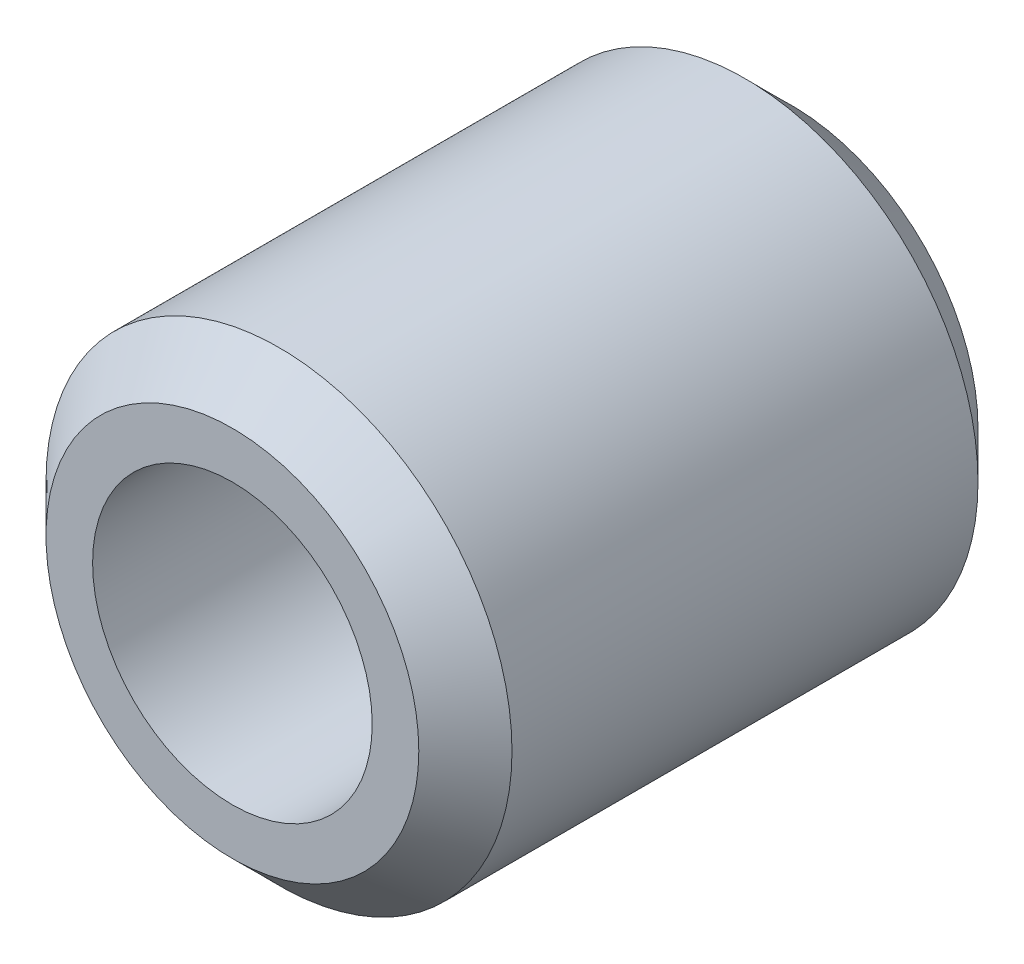
SolidWorks part; units mm, degrees
material "Alloy Steel"
ref_plane "Front Plane" through (0, 0, 0) normal (0, 0, 1) x (1, 0, 0)
ref_plane "Top Plane" through (0, 0, 0) normal (0, 1, 0) x (1, 0, 0)
ref_plane "Right Plane" through (0, 0, 0) normal (1, 0, 0) x (0, 0, -1)
sketch "Sketch1" plane through (0, 0, 0) normal (0, 0, 1) x (1, 0, 0)
  circle A0 centre (0, 0) radius 4.7625
  dimension "D1" = 9.525
extrude "Boss-Extrude1" add sketch "Sketch1" against normal blind 19.05
sketch "Sketch2" plane through (0, 0, 0) normal (0, 0, 1) x (1, 0, 0)
  circle A0 centre (0, 0) radius 7.9375
  dimension "D1" = 15.875
extrude "Boss-Extrude2" add sketch "Sketch2" against normal blind 19.05
sketch "Sketch3" plane through (0, 0, 0) normal (0, 0, 1) x (1, 0, 0)
  circle A0 centre (0, 0) radius 4.7625
  dimension "D1" = 9.525
extrude "Cut-Extrude1" cut sketch "Sketch3" against normal blind 12.7
chamfer "Chamfer1" distance 1.5875 angle 45 2 edges at (7.9375, 0, -19.05) (7.9375, 0, 0)
